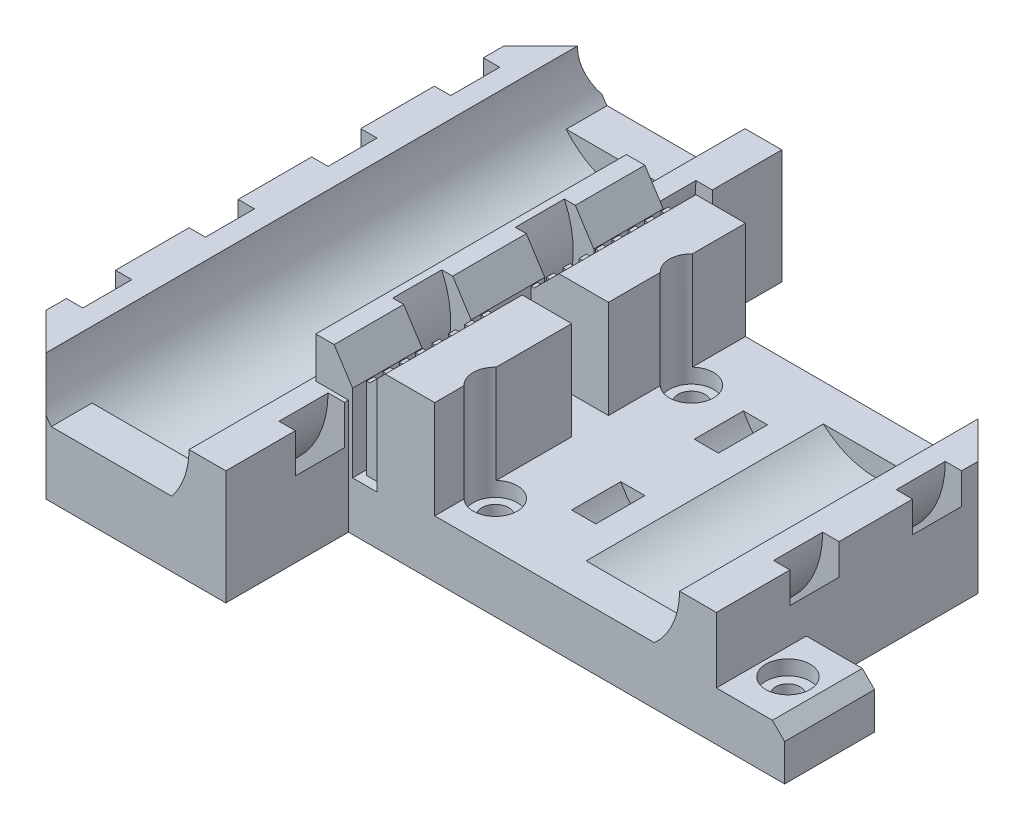
SolidWorks part; units mm, degrees
material "PBT General Purpose"
ref_plane "Front Plane" through (0, 0, 0) normal (0, 0, 1) x (1, 0, 0)
ref_plane "Top Plane" through (0, 0, 0) normal (0, 1, 0) x (1, 0, 0)
ref_plane "Right Plane" through (0, 0, 0) normal (1, 0, 0) x (0, 0, -1)
sketch "Sketch1" plane through (0, 0, 0) normal (0, 1, 0) x (1, 0, 0)
  line L0 (0.3879, -8.2154) -> (0.3879, 6.7846)
  line L1 (-27.6121, -8.2154) -> (0.3879, -8.2154)
  line L2 (-27.6121, -8.2154) -> (-27.6121, 59.7846)
  line L3 (-27.6121, 59.7846) -> (0.3879, 59.7846)
  line L4 (0.3879, 6.7846) -> (53.7379, 6.7846)
  line L5 (53.7379, 6.7846) -> (53.7379, 17.7846)
  line L6 (45.3879, 44.7846) -> (0.3879, 44.7846)
  line L7 (0.3879, 44.7846) -> (0.3879, 59.7846)
  line L8 (53.7379, 17.7846) -> (45.3879, 17.7846)
  line L9 (45.3879, 44.7846) -> (45.3879, 17.7846)
  circle A0 centre (12.7879, 36.3346) radius 1.65
  circle A1 centre (12.7879, 12.3346) radius 1.65
  circle A2 centre (48.5879, 12.3346) radius 1.5
  dimension "D10" = 3.3
  dimension "D13" = 3.3
  dimension "D15" = 3
  dimension "D1" = 68
  dimension "D2" = 28
  dimension "D3" = 15
  dimension "D4" = 15
  dimension "D5" = 53.35
  dimension "D6" = 28
  dimension "D7" = 45
  dimension "D8" = 11
  dimension "D9" = 24
  dimension "D11" = 40.4
  dimension "D12" = 40.4
  dimension "D14" = 8.45
  dimension "D16" = 32.45
  dimension "D17" = 35.8
extrude "Boss-Extrude1" add sketch "Sketch1" along normal blind 19
sketch "Sketch2" plane through (0, 19, 0) normal (0, 1, 0) x (1, 0, 0)
  line L1 (-27.6121, 59.7846) -> (0.3879, 59.7846)
  line L2 (-27.6121, 59.7846) -> (-27.6121, -8.2154)
  line L3 (-27.6121, -8.2154) -> (0.3879, -8.2154)
  line L4 (0.3879, 59.7846) -> (0.3879, -8.2154)
extrude "Cut-Extrude1" cut sketch "Sketch2" against normal blind 5
sketch "Sketch3" plane through (0, 0, 8.2154) normal (0, 0, 1) x (1, 0, 0)
  line L1 (-27.6121, 14) -> (0.3879, 14) construction
  line L2 (0.3879, 14) -> (0.3879, 0) construction
  circle A0 centre (-13.6121, 14) radius 9.5
  dimension "D2" = 19
  dimension "D1" = 0
  dimension "D3" = 14
extrude "Cut-Extrude2" cut sketch "Sketch3" against normal blind 79.7876
sketch "Sketch4" plane through (0, 0, 0) normal (0, -1, 0) x (1, 0, 0)
  line L0 (0.3879, 8.2154) -> (0.3879, -6.7846) construction
  line L1 (-27.6121, 8.2154) -> (0.3879, 8.2154)
  line L2 (-27.6121, 8.2154) -> (-27.6121, 3.2154)
  line L3 (-27.6121, 3.2154) -> (0.3879, 3.2154)
  line L4 (0.3879, 8.2154) -> (0.3879, 3.2154)
  line L5 (0.3879, -44.7846) -> (0.3879, -59.7846) construction
  line L6 (-27.6121, -59.7846) -> (0.3879, -59.7846)
  line L7 (-27.6121, -59.7846) -> (-27.6121, -54.7846)
  line L8 (-27.6121, -54.7846) -> (0.3879, -54.7846)
  line L9 (0.3879, -59.7846) -> (0.3879, -54.7846)
  dimension "D1" = 5
  dimension "D2" = 5
extrude "Boss-Extrude3" add sketch "Sketch4" against normal blind 8
sketch "Sketch5" plane through (0, 14, 0) normal (0, 1, 0) x (1, 0, 0)
  line L0 (-23.1121, 59.7846) -> (-23.1121, -8.2154) construction
  line L1 (-25.6121, 0.2846) -> (-28.4121, 0.2846)
  line L2 (-25.6121, 0.2846) -> (-25.6121, 6.2846)
  line L3 (-25.6121, 6.2846) -> (-28.4121, 6.2846)
  line L4 (-28.4121, 0.2846) -> (-28.4121, 6.2846)
  line L5 (-20.9776, -3.2154) -> (-6.2466, -3.2154) construction
  dimension "D1" = 6
  dimension "D2" = 2.8
  dimension "D3" = 2.5
  dimension "D4" = 3.5
ref_axis "Axis1" through (-13.6121, 14, -59.7846) along (0, 0, 1)
revolve "Cut-Revolve2" cut sketch "Sketch5" angle 360 about axis through (-13.6121, 14, -59.7846) along (0, 0, 1)
sketch "Sketch7" plane through (0, 14, 0) normal (0, 1, 0) x (1, 0, 0)
  line L0 (0.3879, 44.7846) -> (0.3879, 6.7846)
  line L1 (0.3879, 44.7846) -> (-3.6121, 44.7846)
  line L2 (0.3879, 6.7846) -> (-3.6121, 6.7846)
  line L3 (-3.6121, 44.7846) -> (-3.6121, 6.7846)
  dimension "D1" = 4
extrude "Boss-Extrude4" add sketch "Sketch7" along normal blind 5
sketch "Sketch8" plane through (0, 19, 0) normal (0, 1, 0) x (1, 0, 0)
  line L0 (-3.6121, 6.7846) -> (53.7379, 6.7846) construction
  line L1 (0.8879, 6.7846) -> (1.4879, 6.7846)
  line L2 (0.8879, 6.7846) -> (0.8879, 44.7846)
  line L3 (0.8879, 44.7846) -> (1.4879, 44.7846)
  line L4 (1.4879, 6.7846) -> (1.4879, 44.7846)
  line L5 (45.3879, 44.7846) -> (-3.6121, 44.7846) construction
  line L6 (0.3879, 44.7846) -> (0.3879, 59.7846) construction
  dimension "D1" = 0.5
  dimension "D2" = 0.6
extrude "Cut-Extrude3" cut sketch "Sketch8" against normal blind 13
pattern_linear "LPattern1" count 4 spacing 15 along (0, 0, -1) of "Cut-Revolve2"
sketch "Sketch9" plane through (0, 0, -6.7846) normal (0, 0, 1) x (1, 0, 0)
  line L0 (0.8879, 19) -> (-1.3621, 19)
  line L1 (0.8879, 6) -> (0.8879, 19) construction
  line L2 (-3.6121, 19) -> (0.8879, 19) construction
  line L3 (-1.3621, 19) -> (0.8879, 15.5)
  line L4 (0.8879, 15.5) -> (0.8879, 19)
extrude "Cut-Extrude4" cut sketch "Sketch9" against normal blind 54
sketch "Sketch11" plane through (0, 0, -6.7846) normal (0, 0, 1) x (1, 0, 0)
  line L0 (0.3879, 0) -> (53.7379, 0) construction
  circle A0 centre (31.3879, 14) radius 9.5
  dimension "D1" = 19
  dimension "D2" = 45
  dimension "D3" = 14
extrude "Cut-Extrude6" cut sketch "Sketch11" along direction (0, 0, -1) on the side against the normal offset from surface (75 mm away) 75
ref_axis "Axis2" through (31.3879, 14, -44.7846) along (0, 0, 1)
sketch "Sketch12" plane through (0, 19, 0) normal (0, 1, 0) x (1, 0, 0)
  line L0 (23.3101, 44.7846) -> (1.4879, 44.7846) construction
  line L1 (10.9379, 44.7846) -> (31.3879, 44.7846)
  line L2 (10.9379, 44.7846) -> (10.9379, 6.7846)
  line L3 (10.9379, 6.7846) -> (31.3879, 6.7846)
  line L4 (31.3879, 44.7846) -> (31.3879, 6.7846)
  line L5 (31.3879, 44.7846) -> (31.3879, 6.7846) construction
  line L6 (1.4879, 6.7846) -> (1.4879, 44.7846) construction
  dimension "D1" = 0
  dimension "D2" = 9.45
extrude "Cut-Extrude7" cut sketch "Sketch12" against normal blind 12
sketch "Sketch14" plane through (0, 19, 0) normal (0, 1, 0) x (1, 0, 0)
  line L1 (39.4656, 44.7846) -> (53.7379, 44.7846)
  line L2 (39.4656, 44.7846) -> (39.4656, 6.7846)
  line L3 (39.4656, 6.7846) -> (53.7379, 6.7846)
  line L4 (53.7379, 44.7846) -> (53.7379, 6.7846)
extrude "Cut-Extrude9" cut sketch "Sketch14" against normal blind 5
sketch "Sketch15" plane through (0, 14, 0) normal (0, 1, 0) x (1, 0, 0)
  line L0 (40.8879, 6.7846) -> (53.7379, 6.7846) construction
  line L1 (53.7379, 17.7846) -> (45.3879, 17.7846)
  line L2 (53.7379, 17.7846) -> (53.7379, 6.7846)
  line L3 (53.7379, 6.7846) -> (45.3879, 6.7846)
  line L4 (45.3879, 17.7846) -> (45.3879, 6.7846)
extrude "Cut-Extrude10" cut sketch "Sketch15" against normal blind 8
sketch "Sketch16" plane through (0, 0, 0) normal (0, -1, 0) x (-1, 0, 0)
  line L0 (-0.3879, 6.7846) -> (-53.7379, 6.7846) construction
  line L1 (-44.6036, 6.7846) -> (-16.2094, 6.7846)
  line L2 (-44.6036, 6.7846) -> (-44.6036, 11.2846)
  line L3 (-44.6036, 11.2846) -> (-16.2094, 11.2846)
  line L4 (-16.2094, 6.7846) -> (-16.2094, 11.2846)
  line L6 (-45.3879, 44.7846) -> (-21.7206, 44.7846)
  line L7 (-45.3879, 44.7846) -> (-45.3879, 40.2846)
  line L8 (-45.3879, 40.2846) -> (-21.7206, 40.2846)
  line L9 (-21.7206, 44.7846) -> (-21.7206, 40.2846)
  dimension "D1" = 4.5
  dimension "D2" = 4.5
extrude "Boss-Extrude5" add sketch "Sketch16" against normal blind 7
sketch "Sketch17" plane through (0, 14, 0) normal (0, 1, 0) x (1, 0, 0)
  line L0 (40.8879, 44.7846) -> (40.8879, 6.7846) construction
  line L1 (43.3879, 21.7846) -> (45.8879, 21.7846)
  line L2 (43.3879, 21.7846) -> (43.3879, 15.7846)
  line L3 (43.3879, 15.7846) -> (45.8879, 15.7846)
  line L4 (45.8879, 21.7846) -> (45.8879, 15.7846)
  line L5 (24.9653, 11.2846) -> (37.8105, 11.2846) construction
  dimension "D1" = 2.5
  dimension "D2" = 6
  dimension "D3" = 2.5
  dimension "D4" = 4.5
revolve "Cut-Revolve3" cut sketch "Sketch17" angle 360 about axis through (31.3879, 14, -44.7846) along (0, 0, 1)
pattern_linear "LPattern2" count 2 spacing 15 along (0, 0, -1) of "Cut-Revolve3"
sketch "Sketch18" plane through (0, 6, 0) normal (0, 1, 0) x (1, 0, 0)
  circle A0 centre (48.5879, 12.3346) radius 2.7
  dimension "D1" = 5.4
extrude "Cut-Extrude11" cut sketch "Sketch18" against normal blind 1.8
sketch "Sketch19" plane through (0, 7, 0) normal (0, 1, 0) x (1, 0, 0)
  circle A0 centre (12.7879, 36.3346) radius 2.7
  circle A1 centre (12.7879, 12.3346) radius 2.7
  dimension "D1" = 5.4
  dimension "D2" = 5.4
extrude "Cut-Extrude12" cut sketch "Sketch19" against normal blind 13.8 from offset 12
sketch "Sketch20" plane through (0, 19, 0) normal (0, 1, 0) x (1, 0, 0)
  line L0 (1.4879, 6.7846) -> (1.4879, 44.7846) construction
  line L1 (3.8879, 42.7846) -> (1.4879, 42.7846)
  line L2 (3.8879, 42.7846) -> (3.8879, 43.8946)
  line L3 (3.8879, 43.8946) -> (1.4879, 43.8946)
  line L4 (1.4879, 42.7846) -> (1.4879, 43.8946)
  line L5 (10.9379, 44.7846) -> (1.4879, 44.7846) construction
  dimension "D1" = 1.11
  dimension "D2" = 2.4
  dimension "D3" = 0.89
extrude "Cut-Extrude13" cut sketch "Sketch20" against normal up to surface (13 mm away) up to face at (1.1879, 6, -25.7846)
pattern_linear "LPattern3" count 20 spacing 2 along (0, 0, 1) of "Cut-Extrude13"
sketch "Sketch23" plane through (0, 0, -6.7846) normal (0, 0, 1) x (1, 0, 0)
  line L1 (10.9379, 19) -> (1.2977, 19)
  line L2 (10.9379, 19) -> (10.9379, 7)
  line L3 (10.9379, 7) -> (1.2977, 7)
  line L4 (1.2977, 19) -> (1.2977, 7)
extrude "Cut-Extrude15" cut sketch "Sketch23" against normal mid plane 4.5 from offset 19 offset against normal yes
chamfer "Chamfer2" distance 1.5 angle 45 1 edges at (53.7379, 6, -12.2846)
chamfer "Chamfer3" distance 6 angle 45 3 edges at (45.3879, 7, -44.7846) (-27.6121, 7, -59.7846) (-27.6121, 7, 8.2154)
sketch "Sketch24" plane through (0, 0, -44.7846) normal (0, 0, -1) x (-1, 0, 0)
  line L0 (-1.4879, 19) -> (-1.4879, 16)
  line L1 (-1.4879, 6) -> (-1.4879, 19) construction
  line L2 (-1.4879, 16) -> (-1.8879, 16)
  line L3 (-1.8879, 16) -> (-4.8879, 19)
  line L4 (-10.9379, 19) -> (-1.4879, 19) construction
  line L5 (-4.8879, 19) -> (-1.4879, 19)
  dimension "D1" = 3
  dimension "D2" = 0.4
extrude "Cut-Extrude16" cut sketch "Sketch24" against normal blind 56
